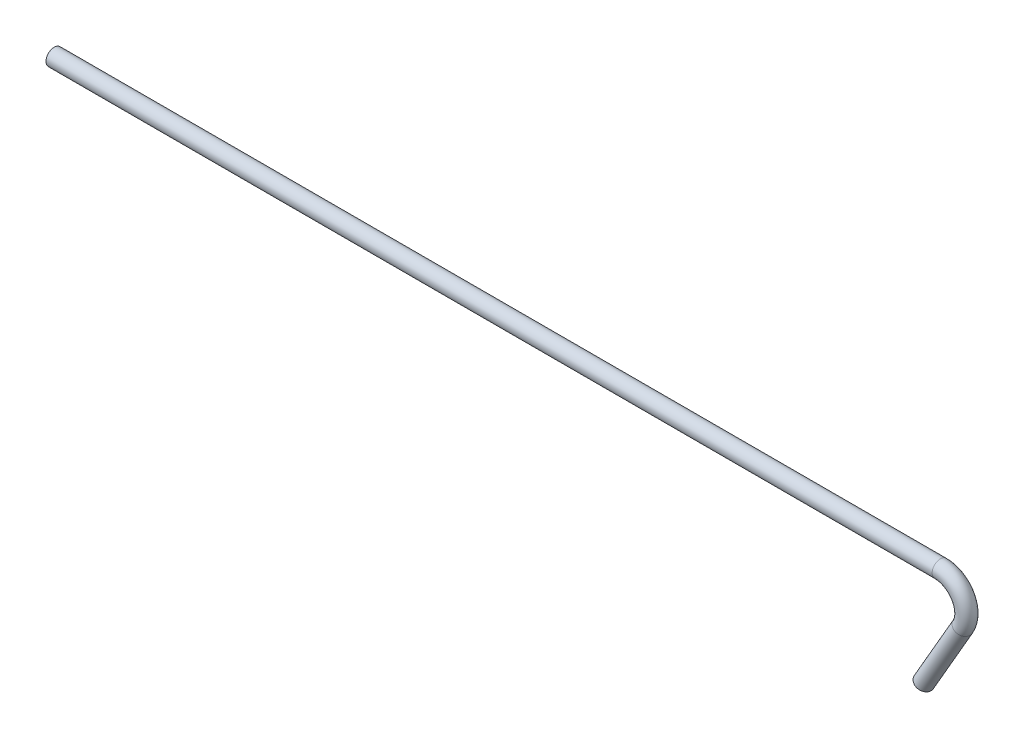
SolidWorks part; units mm, degrees
ref_plane "Front" through (0, 0, 0) normal (0, 0, 1) x (1, 0, 0)
ref_plane "Top" through (0, 0, 0) normal (0, 1, 0) x (1, 0, 0)
ref_plane "Right" through (0, 0, 0) normal (1, 0, 0) x (0, 0, -1)
sketch "Sketch1" plane through (0, 0, 0) normal (0, 0, 1) x (1, 0, 0)
  line L0 (0, 0) -> (215.9, 0)
  line L1 (221.3993, -9.525) -> (211.8993, -25.9795)
  arc A0 (221.3993, -9.525) -> (215.9, 0) centre (215.9, -6.35) ccw
  dimension "D1" = 6.35
  dimension "D2" = 215.9
  dimension "D3" = 60
  dimension "D4" = 19
sketch "Sketch2" plane through (0, 0, 0) normal (1, 0, 0) x (0, 0, -1)
  circle A0 centre (0, 0) radius 2
  dimension "D1" = 4
sweep "Sweep1" add profiles "Sketch2" path "Sketch1"
